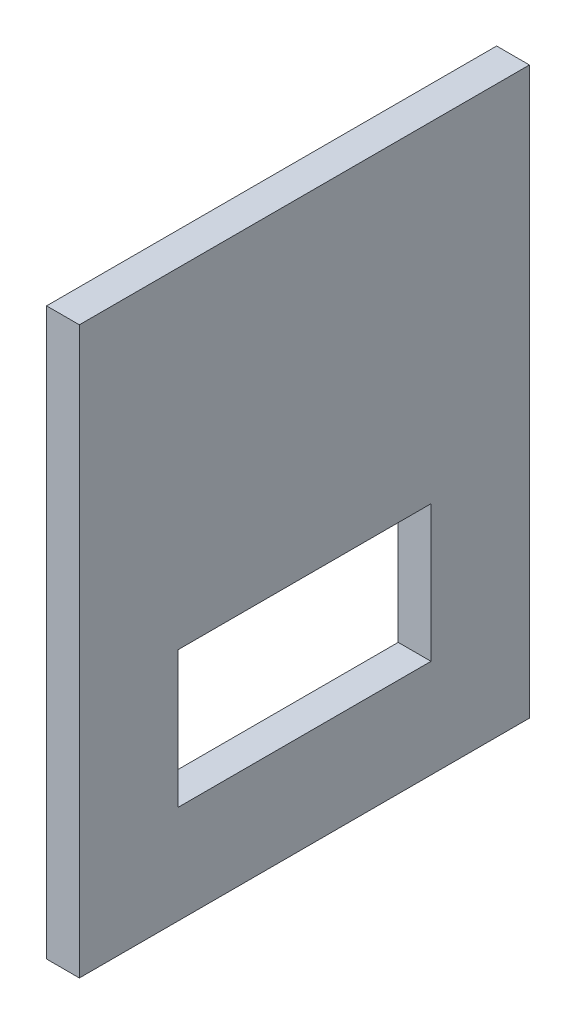
SolidWorks part; units mm, degrees
ref_plane "Front Plane" through (0, 0, 0) normal (0, 0, 1) x (1, 0, 0)
ref_plane "Top Plane" through (0, 0, 0) normal (0, 1, 0) x (1, 0, 0)
ref_plane "Right Plane" through (0, 0, 0) normal (1, 0, 0) x (0, 0, -1)
sketch "Sketch1" plane through (0, 0, 0) normal (0, 0, 1) x (1, 0, 0)
  line L1 (0, 0) -> (5, 0)
  line L2 (0, 0) -> (0, 86.2)
  line L3 (0, 86.2) -> (5, 86.2)
  line L4 (5, 0) -> (5, 86.2)
extrude "Boss-Extrude1" add sketch "Sketch1" along normal blind 68.58
sketch "Sketch3" plane through (0, 0, 0) normal (-1, 0, 0) x (0, 0, 1)
  line L1 (15, 15) -> (53.58, 15)
  line L2 (15, 15) -> (15, 35.8)
  line L3 (15, 35.8) -> (53.58, 35.8)
  line L4 (53.58, 15) -> (53.58, 35.8)
extrude "Cut-Extrude2" cut sketch "Sketch3" against normal blind 5
